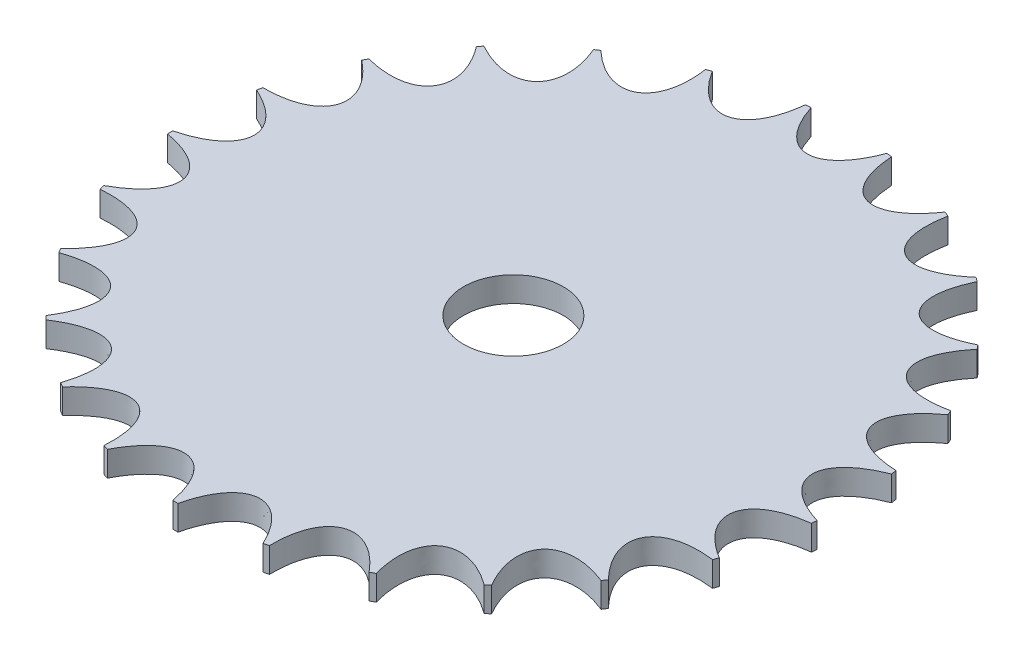
SolidWorks part; units mm, degrees
ref_plane "Front Plane" through (0, 0, 0) normal (0, 0, 1) x (1, 0, 0)
ref_plane "Top Plane" through (0, 0, 0) normal (0, 1, 0) x (1, 0, 0)
ref_plane "Right Plane" through (0, 0, 0) normal (1, 0, 0) x (0, 0, -1)
sketch "Sketch1" plane through (0, 0, 0) normal (0, 1, 0) x (1, 0, 0)
  line L0 (0, 0) -> (14.0773, 22.4517) construction
  line L1 (0, 0) -> (19.2186, 18.2454) construction
  line L2 (0, 0) -> (17.7301, 21.6713) construction
  circle A0 centre (0, 0) radius 26.5
  circle A1 centre (0, 0) radius 28 construction
  circle A2 centre (0, 0) radius 23 construction
  dimension "D1" = 53
  dimension "D2" = 46
  dimension "D3" = 14.4
  dimension "D4" = 7.2
extrude "Boss-Extrude1" add sketch "Sketch1" along normal blind 2
sketch "Sketch2" plane through (0, 2, 0) normal (0, 1, 0) x (1, 0, 0)
  line L0 (0, 0) -> (16.0666, 21.074) construction
  line L1 (0, 0) -> (19.633, 19.9636) construction
  line L2 (0, 0) -> (20.8028, 16.4163) construction
  circle A0 centre (0, 0) radius 28 construction
  circle A1 centre (0, 0) radius 23 construction
  arc A2 (20.6706, 16.5824) -> (16.235, 20.9446) centre (0, 0) ccw
  conic Q0 (16.235, 20.9446) -> (20.6706, 16.5824) control (12.1352, 12.3396) rho 0.367334
  dimension "D1" = 14.4
  dimension "D2" = 7.2
extrude "Cut-Extrude1" cut sketch "Sketch2" against normal blind 2
pattern_circular "CirPattern2" count 25 over 360 about axis through (0, 2, 0) along (0, -1, 0) of "Cut-Extrude1"
sketch "Sketch4" plane through (0, 2, 0) normal (0, 1, 0) x (1, 0, 0)
  line L1 (0, 0) -> (0, -3) construction
  circle A1 centre (0, 0) radius 4
  point P8 (0, -3)
  dimension "D1" = 8
  dimension "D2" = 3
extrude "Cut-Extrude2" cut sketch "Sketch4" against normal blind 2
